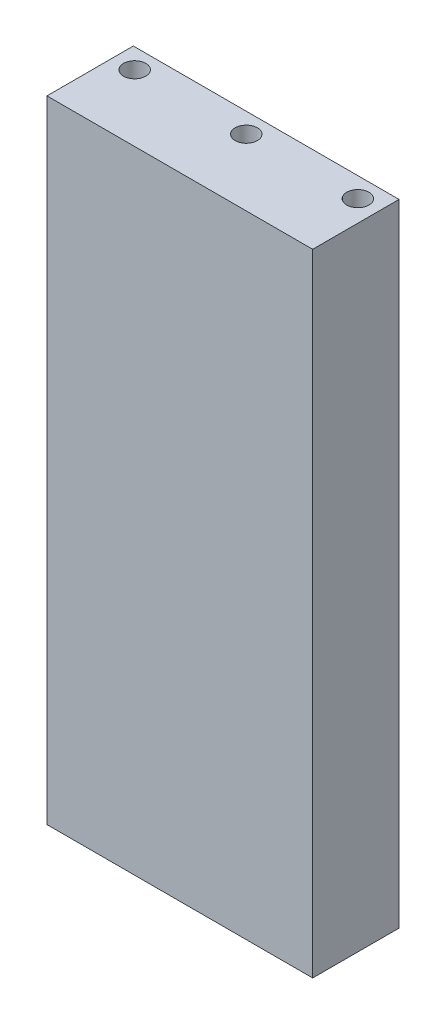
SolidWorks part; units mm, degrees
material "Custom Plastic"
ref_plane "X-Y Datum" through (0, 0, 0) normal (0, 0, 1) x (1, 0, 0)
ref_plane "X-Z Datum" through (0, 0, 0) normal (0, 1, 0) x (1, 0, 0)
ref_plane "Y-Z Datum" through (0, 0, 0) normal (1, 0, 0) x (0, 0, -1)
sketch "Sketch1" plane through (0, 0, 0) normal (0, 1, 0) x (1, 0, 0)
  line L1 (-34.4796, 60.8548) -> (16.3204, 60.8548)
  line L2 (-34.4796, 60.8548) -> (-34.4796, 53.2348)
  line L3 (-34.4796, 53.2348) -> (16.3204, 53.2348)
  line L4 (16.3204, 60.8548) -> (16.3204, 53.2348)
  line L5 (-34.4796, 60.8548) -> (16.3204, 53.2348) construction
  line L6 (-34.4796, 53.2348) -> (16.3204, 60.8548) construction
  circle A0 centre (-30.4156, 57.0448) radius 2.1273
  circle A1 centre (-9.0796, 57.0448) radius 2.1272
  circle A2 centre (12.2564, 57.0448) radius 2.1273
  point P0 (-30.4156, 57.0448)
  point P1 (-9.0796, 57.0448)
  point P2 (12.2564, 57.0448)
  dimension "D1" = 4.2545
  dimension "D2" = 7.62
  dimension "D3" = 50.8
extrude "Boss-Extrude1" add sketch "Sketch1" along normal mid plane 120.65
sketch "Sketch2" plane through (0, 0, 0) normal (0, 1, 0) x (1, 0, 0)
  line L0 (-34.4796, 60.8548) -> (-34.4796, 53.2348) construction
  line L1 (-34.4796, 53.2348) -> (16.3204, 53.2348)
  line L2 (-34.4796, 53.2348) -> (-34.4796, 44.3448)
  line L3 (-34.4796, 44.3448) -> (16.3204, 44.3448)
  line L4 (16.3204, 53.2348) -> (16.3204, 44.3448)
  line L5 (-34.4796, 53.2348) -> (16.3204, 53.2348) construction
  line L6 (16.3204, 53.2348) -> (16.3204, 60.8548) construction
  line L8 (-42.1946, 44.3448) -> (-51.7196, 44.3448)
extrude "Boss-Extrude2" add sketch "Sketch2" along normal mid plane 120.65 contours L4 L1 L2 L3
